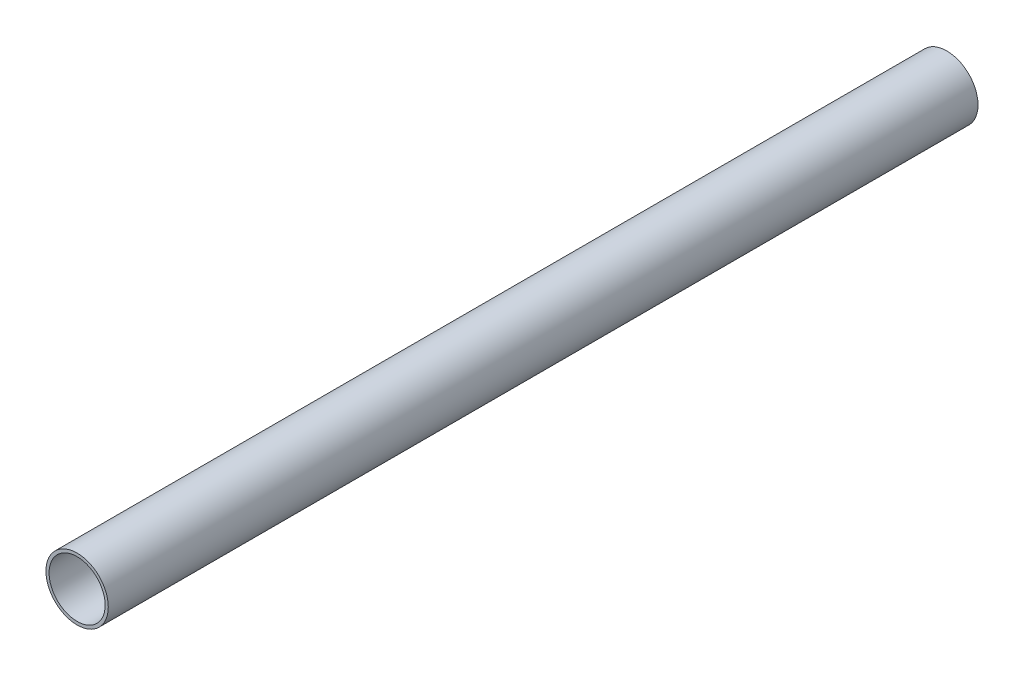
SolidWorks part; units mm, degrees
ref_plane "前视基准面" through (0, 0, 0) normal (0, 0, 1) x (1, 0, 0)
ref_plane "上视基准面" through (0, 0, 0) normal (0, 1, 0) x (1, 0, 0)
ref_plane "右视基准面" through (0, 0, 0) normal (1, 0, 0) x (0, 0, -1)
sketch "草图1" plane through (0, 0, 0) normal (0, 0, 1) x (1, 0, 0)
  circle A0 centre (0, 0) radius 10
  circle A1 centre (0, 0) radius 9
extrude "凸台-拉伸1" add sketch "草图1" along normal blind 279
